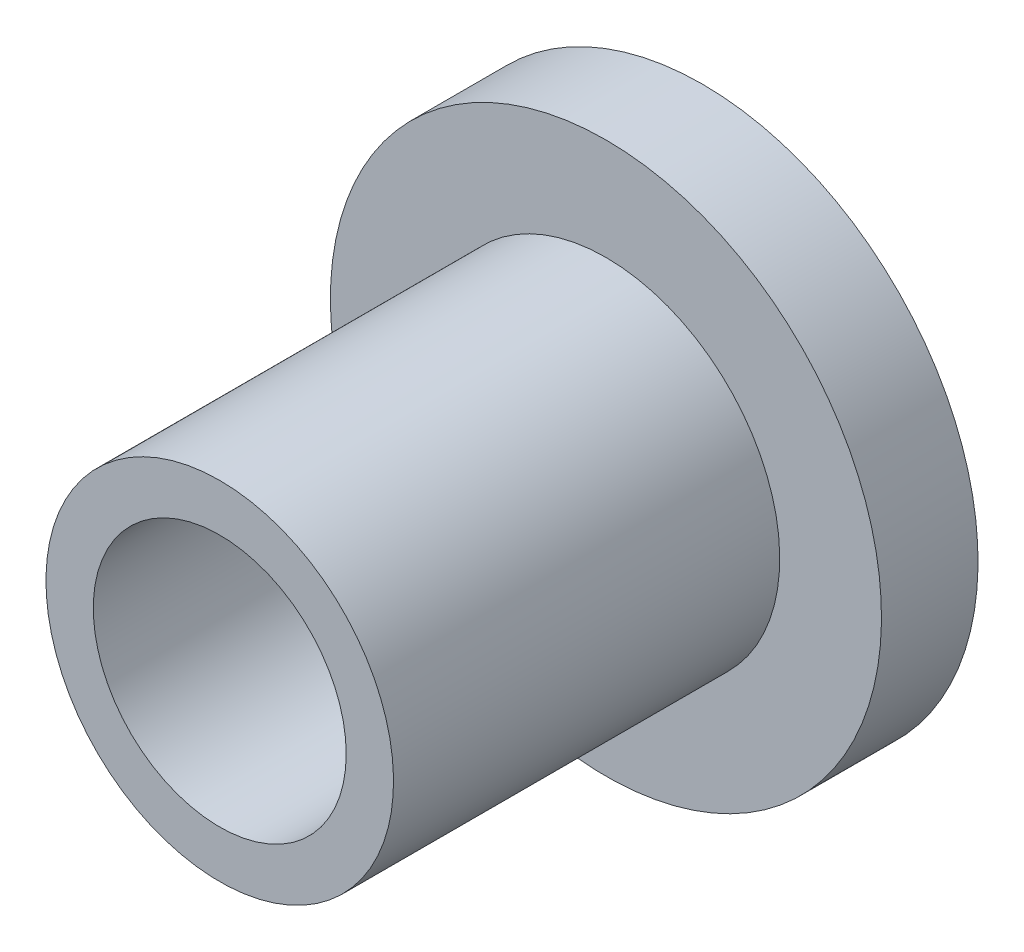
SolidWorks part; units mm, degrees
ref_plane "Front Plane" through (0, 0, 0) normal (0, 0, 1) x (1, 0, 0)
ref_plane "Top Plane" through (0, 0, 0) normal (0, 1, 0) x (1, 0, 0)
ref_plane "Right Plane" through (0, 0, 0) normal (1, 0, 0) x (0, 0, -1)
sketch "Sketch1" plane through (0, 0, 1384.4433) normal (0, 0, -1) x (-1, 0, 0)
  circle A0 centre (-588.4518, 952.7771) radius 9 construction
  circle A1 centre (-588.4518, 952.7771) radius 9
extrude "Boss-Extrude1" add sketch "Sketch1" against normal blind 20
sketch "Sketch2" plane through (0, 0, 1384.4433) normal (0, 0, -1) x (-1, 0, 0)
  circle A0 centre (-588.4518, 952.7771) radius 14.2703
extrude "Boss-Extrude2" add sketch "Sketch2" along normal blind 5
sketch "Sketch3" plane through (0, 0, 1404.4433) normal (0, 0, 1) x (1, 0, 0)
  circle A0 centre (588.4518, 952.7771) radius 6.5497
extrude "Cut-Extrude1" cut sketch "Sketch3" against normal blind 18
